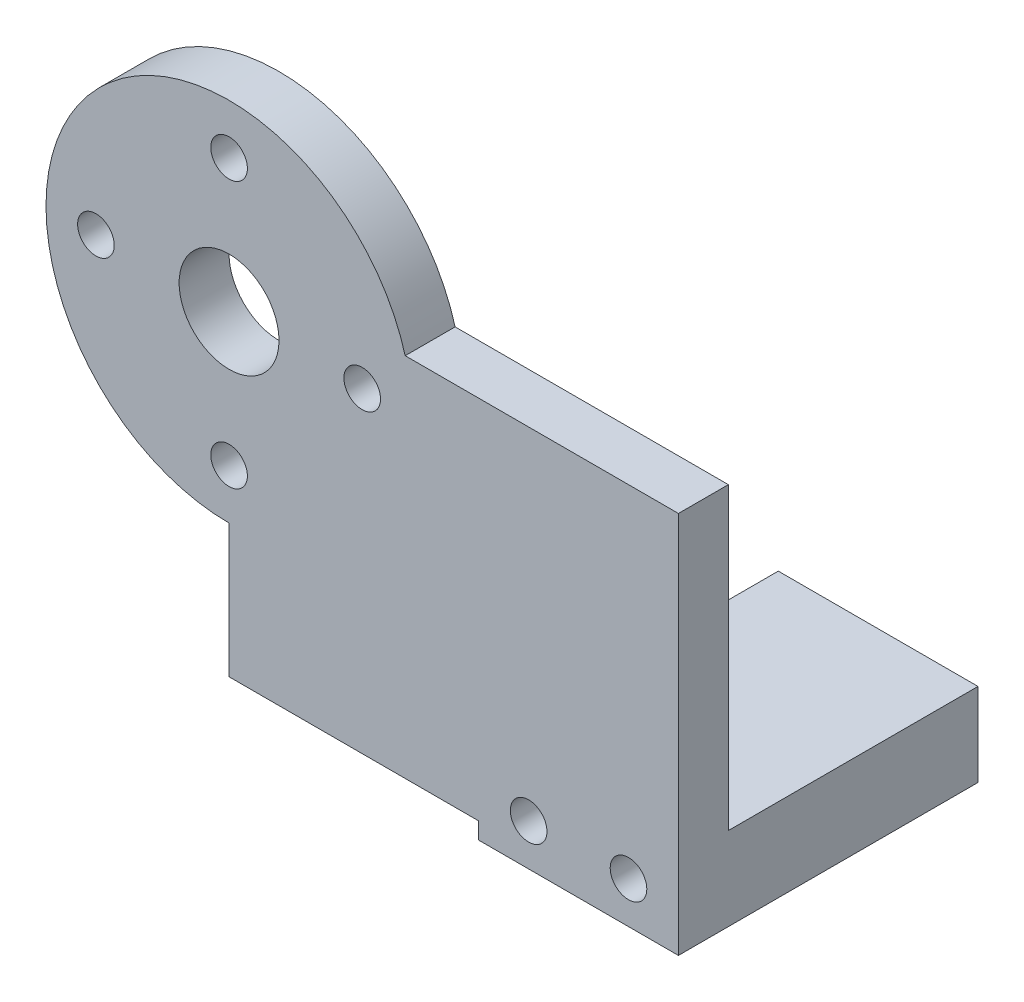
SolidWorks part; units mm, degrees
ref_plane "Front Plane" through (0, 0, 0) normal (0, 0, 1) x (1, 0, 0)
ref_plane "Top Plane" through (0, 0, 0) normal (0, 1, 0) x (1, 0, 0)
ref_plane "Right Plane" through (0, 0, 0) normal (1, 0, 0) x (0, 0, -1)
sketch "Stock_horn_attachment_profile" plane through (0, 0, 0) normal (0, 0, 1) x (1, 0, 0)
  circle A0 centre (0, 0) radius 11
  dimension "D1" = 22
extrude "Stock_horn_attachment" add sketch "Stock_horn_attachment_profile" along normal blind 3 from offset 15
sketch "Finger_arm_profile" plane through (0, 0, 0) normal (0, 0, 1) x (1, 0, 0)
  line L1 (0, -19) -> (27, -19)
  line L2 (0, -19) -> (0, 3)
  line L3 (0, 3) -> (27, 3)
  line L4 (27, -19) -> (27, 3)
  dimension "D1" = 27
  dimension "D2" = 22
extrude "Finger_arm" add sketch "Finger_arm_profile" along normal blind 3 from offset 15
sketch "Descending_contact_finger_profile" plane through (0, 0, 0) normal (0, 0, 1) x (1, 0, 0)
  line L1 (15, -20) -> (27, -20)
  line L2 (15, -20) -> (15, -15)
  line L3 (15, -15) -> (27, -15)
  line L4 (27, -20) -> (27, -15)
  dimension "D1" = 12
  dimension "D2" = 5
extrude "Descending_contact_finger" add sketch "Descending_contact_finger_profile" along normal blind 18
sketch "Horn_center_access_profile" plane through (0, 0, 0) normal (0, 0, 1) x (1, 0, 0)
  circle A0 centre (0, 0) radius 3
  dimension "D1" = 6
extrude "Horn_center_access" cut sketch "Horn_center_access_profile" along normal through all from offset 50
sketch "Horn_screws_profile" plane through (0, 0, 0) normal (0, 0, 1) x (1, 0, 0)
  circle A0 centre (0, -8) radius 1.1
  circle A1 centre (0, 8) radius 1.1
  circle A2 centre (-8, 0) radius 1.1
  circle A3 centre (8, 0) radius 1.1
  dimension "D1" = 2.2
  dimension "D2" = 2.2
  dimension "D3" = 2.2
  dimension "D4" = 2.2
extrude "Horn_screws" cut sketch "Horn_screws_profile" along normal through all from offset 50
sketch "Contact_pad_keeper_profile" plane through (0, 0, 0) normal (0, 0, 1) x (1, 0, 0)
  circle A0 centre (18, -17.5) radius 1.1
  circle A1 centre (24, -17.5) radius 1.1
  dimension "D1" = 2.2
  dimension "D2" = 2.2
extrude "Contact_pad_keeper" cut sketch "Contact_pad_keeper_profile" along normal through all from offset 50
